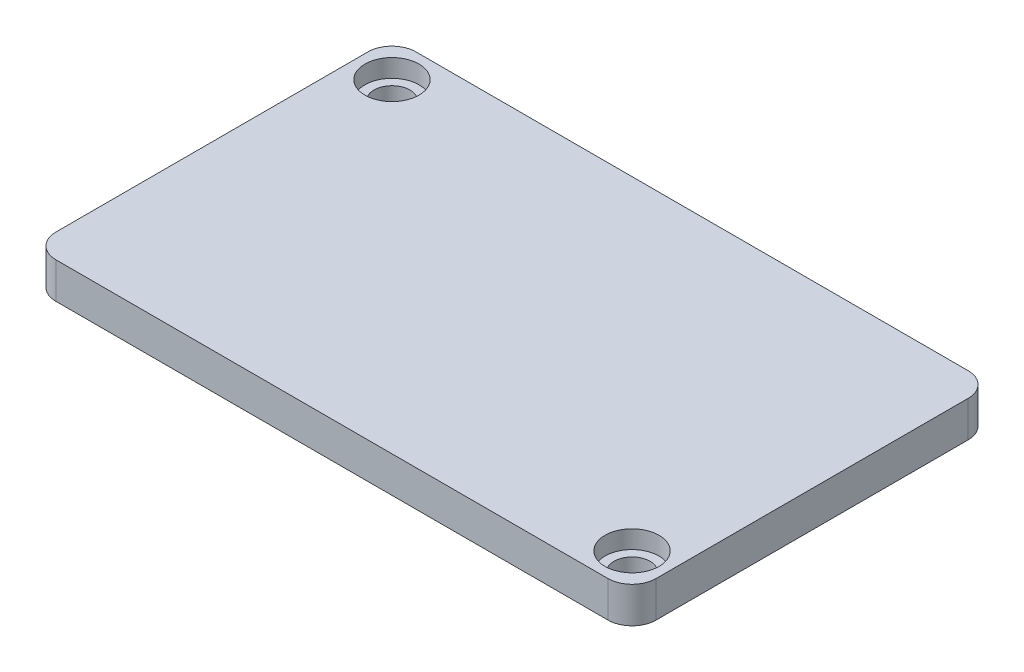
SolidWorks part; units mm, degrees
ref_plane "Alzado" through (0, 0, 0) normal (0, 0, 1) x (1, 0, 0)
ref_plane "Planta" through (0, 0, 0) normal (0, 1, 0) x (1, 0, 0)
ref_plane "Vista lateral" through (0, 0, 0) normal (1, 0, 0) x (0, 0, -1)
sketch "Croquis2" plane through (0, 0, 0) normal (0, 1, 0) x (1, 0, 0)
  line L1 (-25, -15) -> (25, -15)
  line L2 (-25, -15) -> (-25, 15)
  line L3 (-25, 15) -> (25, 15)
  line L4 (25, -15) -> (25, 15)
  line L5 (-25, -15) -> (25, 15) construction
  line L6 (-25, 15) -> (25, -15) construction
  point P0 (0, 0)
  dimension "D1" = 30
  dimension "D2" = 50
extrude "Saliente-Extruir2" add sketch "Croquis2" along normal blind 3
sketch "Croquis3" plane through (0, 0, 0) normal (0, -1, 0) x (1, 0, 0)
  line L5 (25, 15) -> (25, -15) construction
  line L6 (-19, -12) -> (22, -12)
  line L8 (-22, -9) -> (-22, 12)
  line L9 (-25, 15) -> (-19, 15)
  line L10 (-25, 15) -> (-25, 9)
  line L17 (-22, 12) -> (19, 12)
  line L18 (22, -12) -> (22, 9)
  line L19 (-19, -10.3636) -> (19, 10.3636) construction
  line L20 (-22, 12) -> (22, -12) construction
  line L21 (25, -15) -> (-25, -15) construction
  line L23 (22, 9) -> (19, 9)
  line L24 (19, 12) -> (19, 9)
  line L27 (-22, -9) -> (-19, -9)
  line L28 (-19, -12) -> (-19, -9)
  point P0 (0, 0)
  dimension "D1" = 3
  dimension "D2" = 3
extrude "Saliente-Extruir3" add sketch "Croquis3" along normal blind 2
fillet "Redondeo1" radius 2 4 edges at (25, 1.5, 15) (-25, 1.5, -15) (-25, 1.5, 15) (25, 1.5, -15)
sketch "Croquis6" plane through (0, 0, 0) normal (0, -1, 0) x (1, 0, 0)
  line L0 (-25, -13) -> (-25, 13) construction
  line L1 (23, -15) -> (-23, -15) construction
  line L2 (25, 13) -> (25, -13) construction
  line L3 (-23, 15) -> (23, 15) construction
  circle A0 centre (-22, -12) radius 1.5
  circle A1 centre (22, 12) radius 1.5
  dimension "D5" = 3
  dimension "D1" = 3
  dimension "D2" = 3
  dimension "D3" = 3
  dimension "D4" = 3
extrude "Cortar-Extruir2" cut sketch "Croquis6" against normal blind 7
fillet "Redondeo3" radius 2 2 edges at (19, -1, 9) (-19, -1, -9)
sketch "Croquis7" plane through (0, 3, 0) normal (0, 1, 0) x (1, 0, 0)
  circle A0 centre (-22, 12) radius 2.25
  circle A1 centre (22, -12) radius 2.25
  dimension "D1" = 4.5
  dimension "D2" = 4.5
extrude "Cortar-Extruir3" cut sketch "Croquis7" against normal blind 1.5
